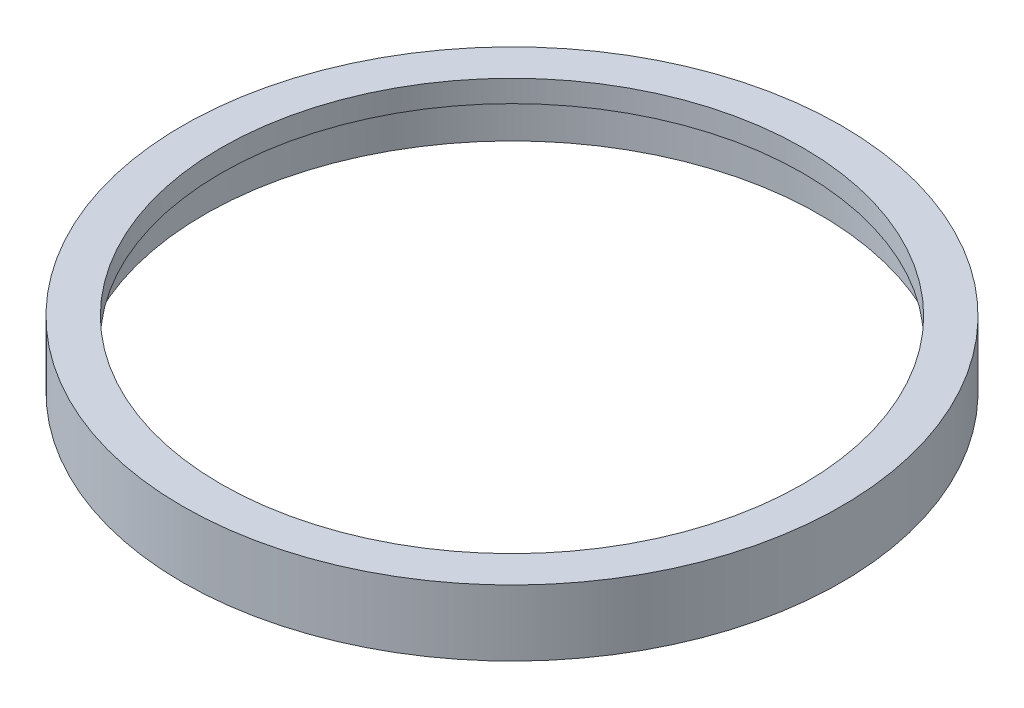
SolidWorks part; units mm, degrees
ref_plane "Alzado" through (0, 0, 0) normal (0, 0, 1) x (1, 0, 0)
ref_plane "Planta" through (0, 0, 0) normal (0, 1, 0) x (1, 0, 0)
ref_plane "Vista lateral" through (0, 0, 0) normal (1, 0, 0) x (0, 0, -1)
sketch "Croquis1" plane through (0, 0, 0) normal (0, 1, 0) x (1, 0, 0)
  circle A0 centre (0, 0) radius 14
  circle A1 centre (0, 0) radius 15
  dimension "D1" = 30
  dimension "D2" = 28
extrude "Saliente-Extruir1" add sketch "Croquis1" along normal blind 2
sketch "Croquis2" plane through (0, 2, 0) normal (0, 1, 0) x (1, 0, 0)
  circle A0 centre (0, 0) radius 13.25
  circle A1 centre (0, 0) radius 15 construction
  circle A2 centre (0, 0) radius 15
  dimension "D1" = 26.5
extrude "Saliente-Extruir2" add sketch "Croquis2" along normal blind 1
